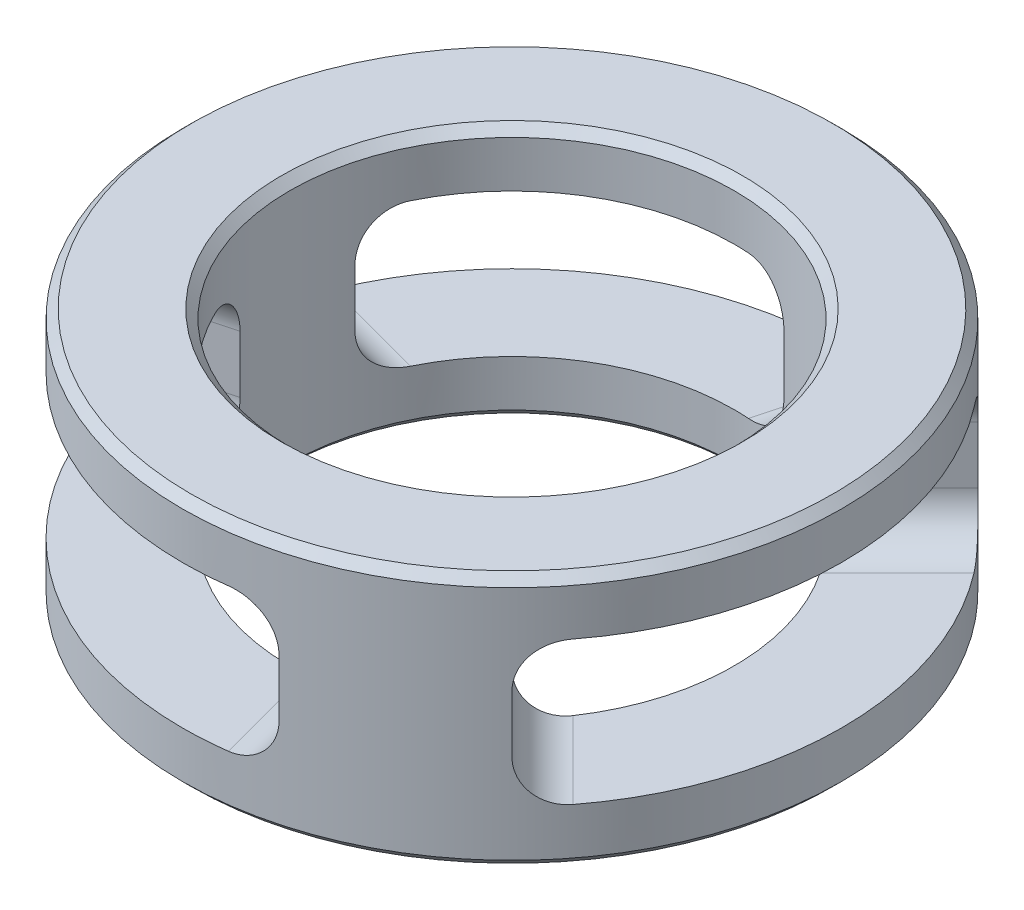
SolidWorks part; units mm, degrees
ref_plane "Front Plane" through (0, 0, 0) normal (0, 0, 1) x (1, 0, 0)
ref_plane "Top Plane" through (0, 0, 0) normal (0, 1, 0) x (1, 0, 0)
ref_plane "Right Plane" through (0, 0, 0) normal (1, 0, 0) x (0, 0, -1)
sketch "Sketch1" plane through (0, 0, 0) normal (0, 1, 0) x (1, 0, 0)
  circle A0 centre (0, 0) radius 11.5
  circle A1 centre (0, 0) radius 7.75
  dimension "D1" = 15.5
  dimension "D2" = 23
extrude "Boss-Extrude1" add sketch "Sketch1" along normal mid plane 8.84
sketch "Sketch2" plane through (0, 0, 0) normal (0, 1, 0) x (1, 0, 0)
  line L0 (0, 0) -> (18.9198, 0) construction
  line L1 (0, 0) -> (12.4953, 12.4953) construction
  line L2 (0, 0) -> (12.4953, -12.4953) construction
  line L3 (4.773, 4.773) -> (8.8388, 8.8388)
  line L4 (4.773, -4.773) -> (8.8388, -8.8388)
  line L5 (1.747, -6.52) -> (3.2352, -12.0741)
  line L6 (-6.52, -1.747) -> (-12.0741, -3.2352)
  line L7 (-6.52, 1.747) -> (-12.0741, 3.2352)
  line L8 (1.747, 6.52) -> (3.2352, 12.0741)
  circle A0 centre (0, 0) radius 6.75 construction
  circle A1 centre (0, 0) radius 11.5 construction
  circle A2 centre (0, 0) radius 12.5 construction
  arc A3 (1.747, -6.52) -> (-6.52, -1.747) centre (0, 0) cw
  circle A4 centre (0, 0) radius 7.75 construction
  arc A5 (4.773, 4.773) -> (4.773, -4.773) centre (0, 0) cw
  arc A6 (8.8388, 8.8388) -> (8.8388, -8.8388) centre (0, 0) cw
  arc A7 (3.2352, -12.0741) -> (-12.0741, -3.2352) centre (0, 0) cw
  arc A8 (-6.52, 1.747) -> (1.747, 6.52) centre (0, 0) cw
  arc A9 (-12.0741, 3.2352) -> (3.2352, 12.0741) centre (0, 0) cw
  point P28 (0, 0)
  dimension "D1" = 1
  dimension "D2" = 1
  dimension "D3" = 90
  dimension "D4" = 3
extrude "Cut-Extrude1" cut sketch "Sketch2" against normal mid plane 5
fillet "Fillet1" radius 1.5 12 edges at (-9.297, 2.5, -2.4911) (-9.297, -2.5, -2.4911) (2.4911, -2.5, -9.297) (2.4911, 2.5, -9.297) (6.8059, -2.5, -6.8059) (6.8059, 2.5, -6.8059) (6.8059, 2.5, 6.8059) (6.8059, -2.5, 6.8059) (2.4911, -2.5, 9.297) (2.4911, 2.5, 9.297) (-9.297, -2.5, 2.4911) (-9.297, 2.5, 2.4911)
chamfer "Chamfer1" distance 0.3 angle 45 4 edges at (0, -4.42, 11.5) (0, 4.42, 11.5) (0, -4.42, 7.75) (0, 4.42, 7.75)
